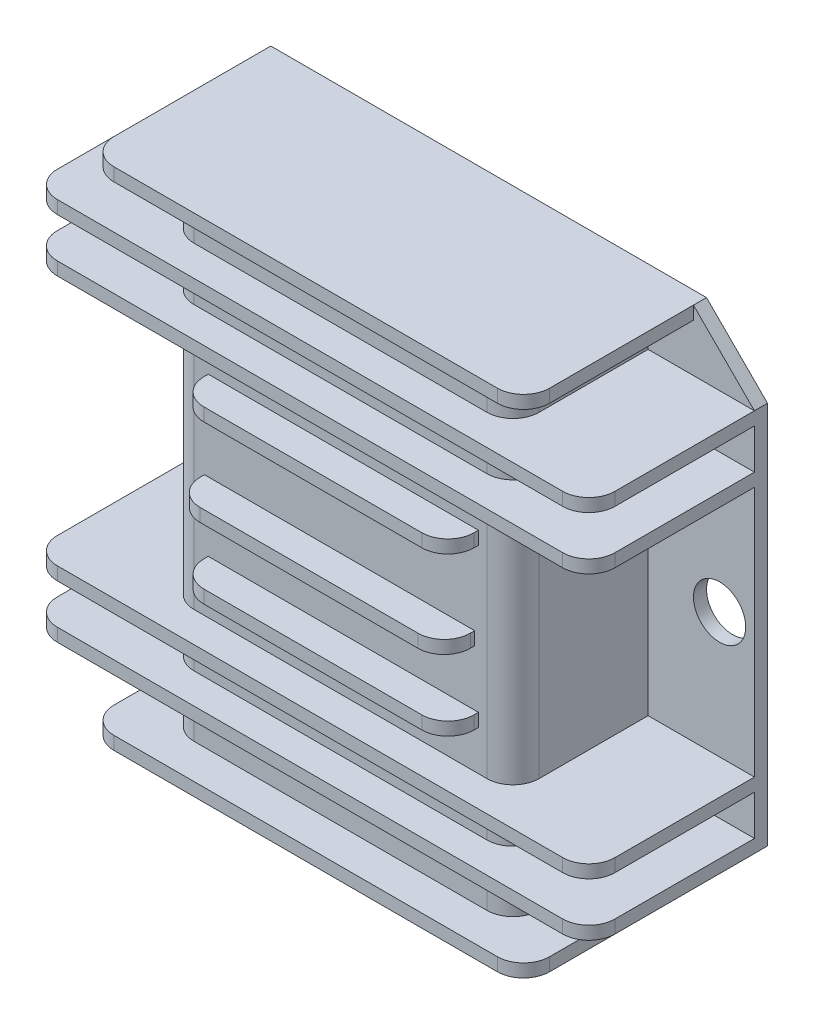
SolidWorks part; units mm, degrees
ref_plane "前视基准面" through (0, 0, 0) normal (0, 0, 1) x (1, 0, 0)
ref_plane "上视基准面" through (0, 0, 0) normal (0, 1, 0) x (1, 0, 0)
ref_plane "右视基准面" through (0, 0, 0) normal (1, 0, 0) x (0, 0, -1)
other "Configuration Table"
ref_plane "基准面1" through (0, 0, 0) normal (0, 0, -1) x (-1, 0, 0)
sketch "草图1" plane through (0, 0, 0) normal (0, 0, -1) x (-1, 0, 0)
  line L0 (32, 29) -> (-32, 29)
  line L1 (-32, 29) -> (-32, -29)
  line L2 (-32, -29) -> (32, -29)
  line L3 (32, -29) -> (32, 29)
  dimension "D1" = 64
  dimension "D2" = 58
extrude "凸台-拉伸1" add sketch "草图1" against normal blind 20.5
sketch "草图2" plane through (32, 0, 0) normal (1, 0, 0) x (0, 0, -1)
  line L0 (-20.5, -15.9) -> (-20.5, -20.5)
  line L1 (-20.5, -20.5) -> (-1.5, -20.5)
  line L2 (-1.5, -20.5) -> (-1.5, -15.9)
  line L3 (-1.5, -15.9) -> (-20.5, -15.9)
  line L4 (0, 29) -> (0, -29) construction
  line L5 (-20.5, 29) -> (0, 29) construction
  dimension "D1" = 1.5
  dimension "D2" = 20.5
  dimension "D3" = 44.9
  dimension "D4" = 49.5
extrude "切除-拉伸1" cut sketch "草图2" against normal through all
sketch "草图3" plane through (32, 0, 0) normal (1, 0, 0) x (0, 0, -1)
  line L0 (-20.5, 14.4) -> (-20.5, -14.4)
  line L1 (-20.5, -14.4) -> (-1.5, -14.4)
  line L2 (-1.5, -14.4) -> (-1.5, 14.4)
  line L3 (-1.5, 14.4) -> (-20.5, 14.4)
  line L4 (-1.5, -20.5) -> (-1.5, -15.9) construction
  line L5 (-1.5, -15.9) -> (-20.5, -15.9) construction
  dimension "D1" = 19
  dimension "D2" = 1.5
  dimension "D3" = 30.3
extrude "切除-拉伸2" cut sketch "草图3" against normal through all
sketch "草图4" plane through (32, 0, 0) normal (1, 0, 0) x (0, 0, -1)
  line L0 (-20.5, 20.5) -> (-20.5, 15.9)
  line L1 (-20.5, 15.9) -> (-1.5, 15.9)
  line L2 (-1.5, 15.9) -> (-1.5, 20.5)
  line L3 (-1.5, 20.5) -> (-20.5, 20.5)
  line L4 (-1.5, -14.4) -> (-1.5, 14.4) construction
  line L5 (-1.5, 14.4) -> (-20.5, 14.4) construction
  dimension "D1" = 19
  dimension "D2" = 1.5
  dimension "D3" = 6.1
extrude "切除-拉伸3" cut sketch "草图4" against normal through all
sketch "草图5" plane through (32, 0, 0) normal (1, 0, 0) x (0, 0, -1)
  line L0 (-20.5, 22) -> (-1.5, 22)
  line L1 (-1.5, 22) -> (-1.5, 29)
  line L2 (-1.5, 29) -> (-20.5, 29)
  line L3 (-20.5, 29) -> (-20.5, 22)
  line L4 (-1.5, 15.9) -> (-1.5, 20.5) construction
  line L5 (-1.5, 20.5) -> (-20.5, 20.5) construction
  dimension "D1" = 19
  dimension "D2" = 1.5
  dimension "D3" = 8.5
extrude "切除-拉伸4" cut sketch "草图5" against normal through all
sketch "草图6" plane through (32, 0, 0) normal (1, 0, 0) x (0, 0, -1)
  line L0 (-1.5, -22) -> (-20.5, -22)
  line L1 (-20.5, -22) -> (-20.5, -29)
  line L2 (-20.5, -29) -> (-1.5, -29)
  line L3 (-1.5, -29) -> (-1.5, -22)
  line L4 (-1.5, -14.4) -> (-1.5, 14.4) construction
  line L5 (-1.5, 14.4) -> (-20.5, 14.4) construction
  dimension "D1" = 19
  dimension "D2" = 36.4
  dimension "D3" = 43.4
extrude "切除-拉伸5" cut sketch "草图6" against normal through all
sketch "草图7" plane through (0, 14.4, 0) normal (0, -1, 0) x (1, 0, 0)
  line L0 (19.8, 17) -> (19.8, 1.5)
  line L1 (19.8, 1.5) -> (-19.8, 1.5)
  line L2 (-19.8, 1.5) -> (-19.8, 17)
  line L3 (-19.8, 17) -> (19.8, 17)
  line L4 (32, 1.5) -> (32, 20.5) construction
  line L5 (-32, 20.5) -> (32, 20.5) construction
  dimension "D1" = 12.2
  dimension "D2" = 51.8
  dimension "D3" = 3.5
  dimension "D4" = 19
extrude "凸台-拉伸2" add sketch "草图7" along normal blind 28.8
sketch "草图8" plane through (0, 0, 1.5) normal (0, 0, 1) x (1, 0, 0)
  line L0 (-25, -27.5) -> (25, -27.5)
  line L1 (25, -27.5) -> (25, -29)
  line L2 (25, -29) -> (-25, -29)
  line L3 (-25, -29) -> (-25, -27.5)
  line L4 (32, -29) -> (32, -22) construction
  line L5 (-32, -22) -> (32, -22) construction
  dimension "D1" = 7
  dimension "D2" = 57
  dimension "D3" = 5.5
  dimension "D4" = 7
extrude "凸台-拉伸3" add sketch "草图8" along normal blind 19.5
sketch "草图9" plane through (0, 0, 1.5) normal (0, 0, 1) x (1, 0, 0)
  line L0 (-25, 29) -> (25, 29)
  line L1 (25, 29) -> (25, 27.5)
  line L2 (25, 27.5) -> (-25, 27.5)
  line L3 (-25, 27.5) -> (-25, 29)
  line L4 (32, 22) -> (32, 29) construction
  line L5 (-32, 29) -> (32, 29) construction
  dimension "D1" = 7
  dimension "D2" = 57
  dimension "D3" = 1.5
extrude "凸台-拉伸4" add sketch "草图9" along normal blind 19.5
sketch "草图10" plane through (0, 0, 17) normal (0, 0, 1) x (1, 0, 0)
  line L0 (15.8306, 9.8) -> (15.8306, 8.3)
  line L1 (15.8306, 8.3) -> (-15.1694, 8.3)
  line L2 (-15.1694, 8.3) -> (-15.1694, 9.8)
  line L3 (-15.1694, 9.8) -> (15.8306, 9.8)
  line L4 (-19.8, -14.4) -> (-19.8, 14.4) construction
  line L5 (19.8, 14.4) -> (-19.8, 14.4) construction
  dimension "D1" = 4.6306
  dimension "D2" = 35.6306
  dimension "D3" = 4.6
  dimension "D4" = 6.1
extrude "凸台-拉伸5" add sketch "草图10" along normal blind 3.5
sketch "草图11" plane through (0, 0, 17) normal (0, 0, 1) x (1, 0, 0)
  line L0 (15.3951, -0.4057) -> (15.3951, -1.9057)
  line L1 (15.3951, -1.9057) -> (-15.6049, -1.9057)
  line L2 (-15.6049, -1.9057) -> (-15.6049, -0.4057)
  line L3 (-15.6049, -0.4057) -> (15.3951, -0.4057)
  line L4 (-19.8, -14.4) -> (-19.8, 14.4) construction
  line L5 (19.8, -14.4) -> (-19.8, -14.4) construction
  dimension "D1" = 4.1951
  dimension "D2" = 35.1951
  dimension "D3" = 12.4943
  dimension "D4" = 13.9943
extrude "凸台-拉伸6" add sketch "草图11" along normal blind 3.5
sketch "草图12" plane through (0, 0, 17) normal (0, 0, 1) x (1, 0, 0)
  line L0 (15.8306, -8.3) -> (15.8306, -9.8)
  line L1 (15.8306, -9.8) -> (-15.1694, -9.8)
  line L2 (-15.1694, -9.8) -> (-15.1694, -8.3)
  line L3 (-15.1694, -8.3) -> (15.8306, -8.3)
  line L4 (-19.8, -14.4) -> (-19.8, 14.4) construction
  line L5 (19.8, 14.4) -> (-19.8, 14.4) construction
  dimension "D1" = 4.6306
  dimension "D2" = 35.6306
  dimension "D3" = 22.7
  dimension "D4" = 24.2
extrude "凸台-拉伸7" add sketch "草图12" along normal blind 3.5
hole_wizard "Ø6.0 (6) 直径孔1" positions "草图14" profile "草图13" hole size "Ø6.0" standard "ANSI Metric"
sketch "草图14" plane through (0, 0, 1.5) normal (0, 0, 1) x (1, 0, 0)
  point P0 (28, 0)
  point P1 (-28, 0)
sketch "草图13" plane through (28, 0, 1.5) normal (1, 0, 0) x (0, -1, 0)
  line L0 (0, 0) -> (0, 1.5)
  line L1 (0, 1.5) -> (3, 1.5)
  line L2 (3, 1.5) -> (3, 0)
  line L5 (3, 0) -> (0, 0)
  line L11 (0, -6.35) -> (0, 107.95) construction
  dimension "通孔孔直径" = 6
  dimension "通孔孔深度" = 1.5
sketch "草图15" plane through (0, 0, 0) normal (1, 0, 0) x (0, 0, -1)
  line L0 (-17, 27.5) -> (-17, 22)
  dimension "D1" = 5.5
rib "筋1" sketch "草图15" sketch "草图15" thickness 39.6 extrusion direction parallel to sketch draft on no parameters "D1"=39.6
ref_plane "基准面2" through (0, 0, 0) normal (-1, 0, 0) x (0, -1, 0)
sketch "草图16" plane through (0, 0, 0) normal (-1, 0, 0) x (0, -1, 0)
  line L0 (27.5, 17) -> (22, 17)
  dimension "D1" = 5.5
rib "筋2" sketch "草图16" sketch "草图16" thickness 39.6 extrusion direction parallel to sketch draft on no parameters "D1"=39.6
sketch "草图17" plane through (0, 0, 0) normal (-1, 0, 0) x (0, -1, 0)
  line L0 (-15.9, 17) -> (-20.5, 17)
  dimension "D1" = 4.6
rib "筋3" sketch "草图17" sketch "草图17" thickness 39.6 extrusion direction parallel to sketch draft on no parameters "D1"=39.6
sketch "草图18" plane through (0, 0, 0) normal (1, 0, 0) x (0, 0, -1)
  line L0 (-17, -15.9) -> (-17, -20.5)
  dimension "D1" = 4.6
rib "筋4" sketch "草图18" sketch "草图18" thickness 39.6 extrusion direction parallel to sketch draft on no parameters "D1"=39.6
chamfer "倒角1" distance 7 angle 45 4 edges at (-32, 29, 0.75) (-32, -29, 0.75) (32, 29, 0.75) (32, -29, 0.75)
fillet "圆角1" radius 3 28 edges at (19.8, 18.2, 17) (15.8306, 9.05, 20.5) (-32, 15.15, 20.5) (-32, -21.25, 20.5) (-15.1694, -9.05, 20.5) (32, -21.25, 20.5) (-25, -28.25, 21) (32, 21.25, 20.5) (25, 28.25, 21) (-32, 21.25, 20.5) (15.3951, -1.1557, 20.5) (32, -15.15, 20.5) (19.8, 24.75, 17) (-32, -15.15, 20.5) (25, -28.25, 21) (-19.8, -18.2, 17) (32, 15.15, 20.5) (-19.8, -24.75, 17) (-25, 28.25, 21) (-19.8, 0, 17) (15.8306, -9.05, 20.5) (-19.8, 24.75, 17) (-15.1694, 9.05, 20.5) (-19.8, 18.2, 17) (-15.6049, -1.1557, 20.5) (19.8, -24.75, 17) (19.8, 0, 17) (19.8, -18.2, 17)
